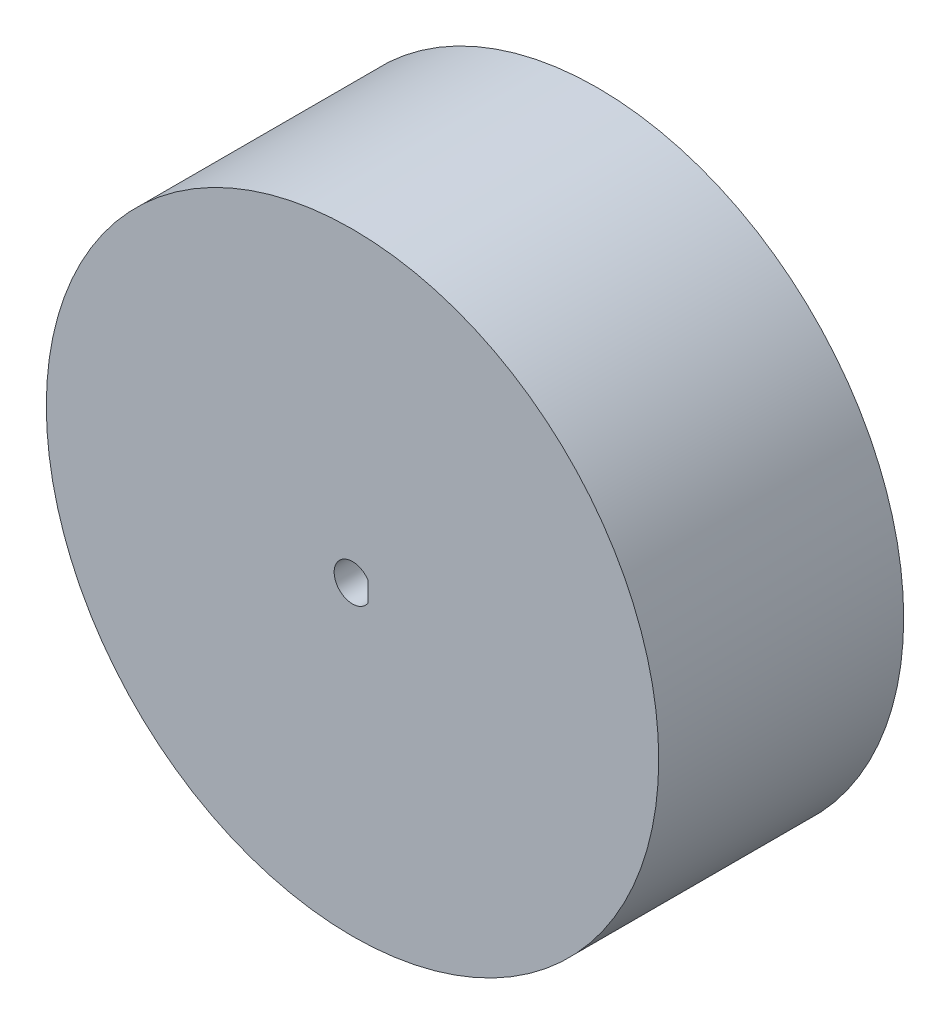
SolidWorks part; units mm, degrees
ref_plane "정면" through (0, 0, 0) normal (0, 0, 1) x (1, 0, 0)
ref_plane "윗면" through (0, 0, 0) normal (0, 1, 0) x (1, 0, 0)
ref_plane "우측면" through (0, 0, 0) normal (1, 0, 0) x (0, 0, -1)
sketch "스케치1" plane through (0, 0, 0) normal (0, 0, 1) x (1, 0, 0)
  line L0 (2.5, -5.3417) -> (2.5, -8.6583)
  circle A0 centre (0, -7) radius 50
  arc A1 (2.5, -5.3417) -> (2.5, -8.6583) centre (0, -7) ccw
  dimension "D1" = 100
extrude "보스-돌출1" add sketch "스케치1" along normal blind 40 contours A0 | A1 L0
